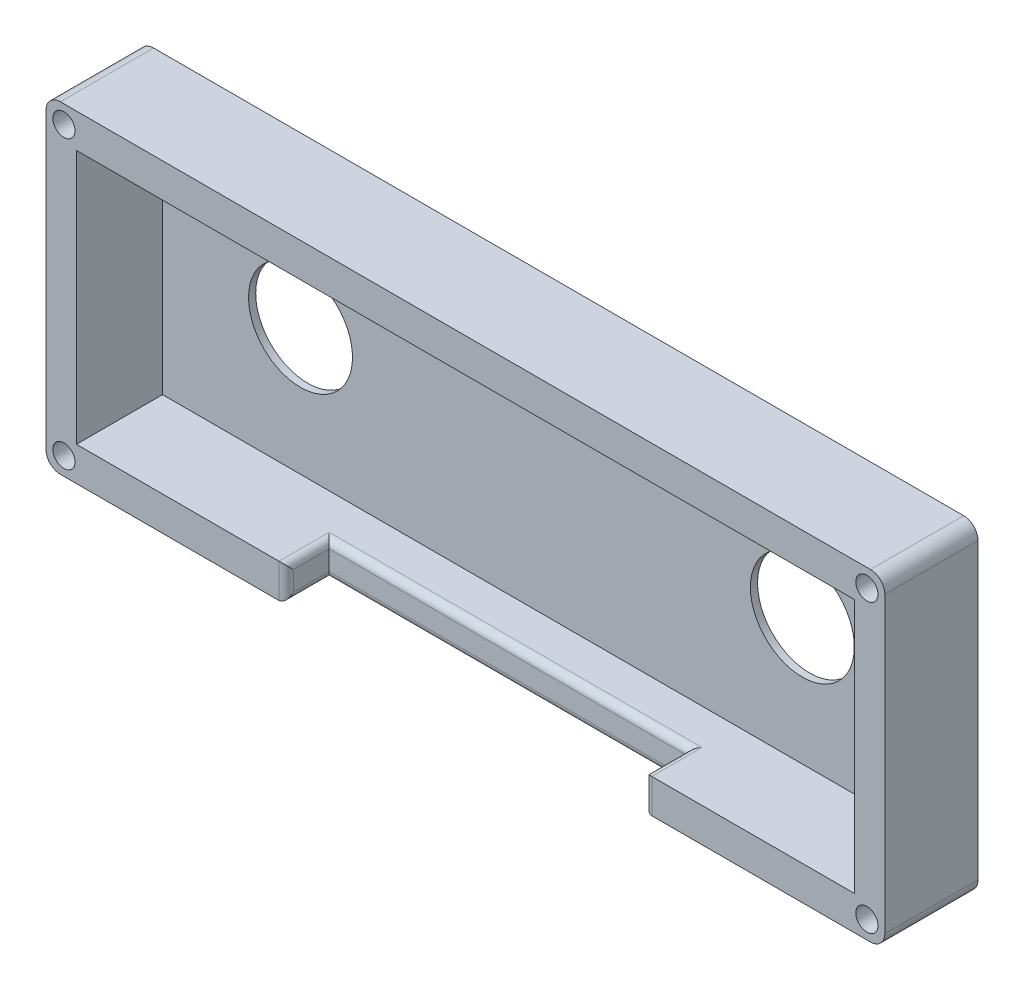
SolidWorks part; units mm, degrees
ref_plane "前视基准面" through (0, 0, 0) normal (0, 0, 1) x (1, 0, 0)
ref_plane "上视基准面" through (0, 0, 0) normal (0, 1, 0) x (1, 0, 0)
ref_plane "右视基准面" through (0, 0, 0) normal (1, 0, 0) x (0, 0, -1)
sketch "草图1" plane through (0, 0, 0) normal (0, 0, 1) x (1, 0, 0)
  line L0 (0, -55) -> (0, 55) construction
  line L1 (-58.5, -22.5) -> (58.5, -22.5)
  line L2 (-58.5, -22.5) -> (-58.5, 22.5)
  line L3 (-58.5, 22.5) -> (58.5, 22.5)
  line L4 (58.5, -22.5) -> (58.5, 22.5)
  line L5 (-58.5, -22.5) -> (58.5, 22.5) construction
  line L6 (-58.5, 22.5) -> (58.5, -22.5) construction
  circle A0 centre (-35, 0) radius 7.25
  circle A1 centre (35, 0) radius 7.25
  point P0 (0, 0)
  point P12 (0, 0)
  dimension "D5" = 14.5
  dimension "D1" = 117
  dimension "D2" = 45
  dimension "D3" = 22.5
  dimension "D4" = 35
extrude "凸台-拉伸1" add sketch "草图1" along normal blind 13
sketch "草图2" plane through (0, 0, 13) normal (0, 0, 1) x (1, 0, 0)
  line L1 (54.25, -17.75) -> (-54.25, -17.75)
  line L2 (54.25, -17.75) -> (54.25, 17.75)
  line L3 (54.25, 17.75) -> (-54.25, 17.75)
  line L4 (-54.25, -17.75) -> (-54.25, 17.75)
  line L5 (54.25, -17.75) -> (-54.25, 17.75) construction
  line L6 (54.25, 17.75) -> (-54.25, -17.75) construction
  point P1 (0, 0)
  dimension "D1" = 108.5
  dimension "D2" = 35.5
extrude "切除-拉伸1" cut sketch "草图2" against normal blind 12
sketch "草图3" plane through (0, 0, 13) normal (0, 0, 1) x (1, 0, 0)
  line L0 (58.5, 22.5) -> (-58.5, 22.5) construction
  line L1 (-58.5, 22.5) -> (-58.5, -22.5) construction
  line L2 (7.15, 0) -> (-7.15, 0) construction
  line L3 (0, -7.15) -> (0, 7.15) construction
  circle A0 centre (-56, 20) radius 1.55
  circle A1 centre (-56, -20) radius 1.55
  circle A2 centre (56, -20) radius 1.55
  circle A3 centre (56, 20) radius 1.55
  dimension "D1" = 2.5
  dimension "D2" = 2.5
extrude "切除-拉伸2" cut sketch "草图3" against normal blind 6
sketch "草图4" plane through (0, 0, 13) normal (0, 0, 1) x (1, 0, 0)
  line L1 (25, -25.2781) -> (-25, -25.2781)
  line L2 (25, -25.2781) -> (25, -14.7219)
  line L3 (25, -14.7219) -> (-25, -14.7219)
  line L4 (-25, -25.2781) -> (-25, -14.7219)
  line L5 (25, -25.2781) -> (-25, -14.7219) construction
  line L6 (25, -14.7219) -> (-25, -25.2781) construction
  point P0 (0, -20)
  dimension "D1" = 50
extrude "切除-拉伸3" cut sketch "草图4" against normal blind 6
fillet "圆角1" radius 2 4 edges at (58.5, -22.5, 6.5) (-58.5, -22.5, 6.5) (58.5, 22.5, 6.5) (-58.5, 22.5, 6.5)
fillet "圆角2" radius 1 8 edges at (-25, -22.5, 10) (-25, -20.125, 13) (25, -20.125, 13) (-25, -17.75, 10) (25, -22.5, 10) (25, -17.75, 10) (0, -22.5, 7) (0, -17.75, 7)
